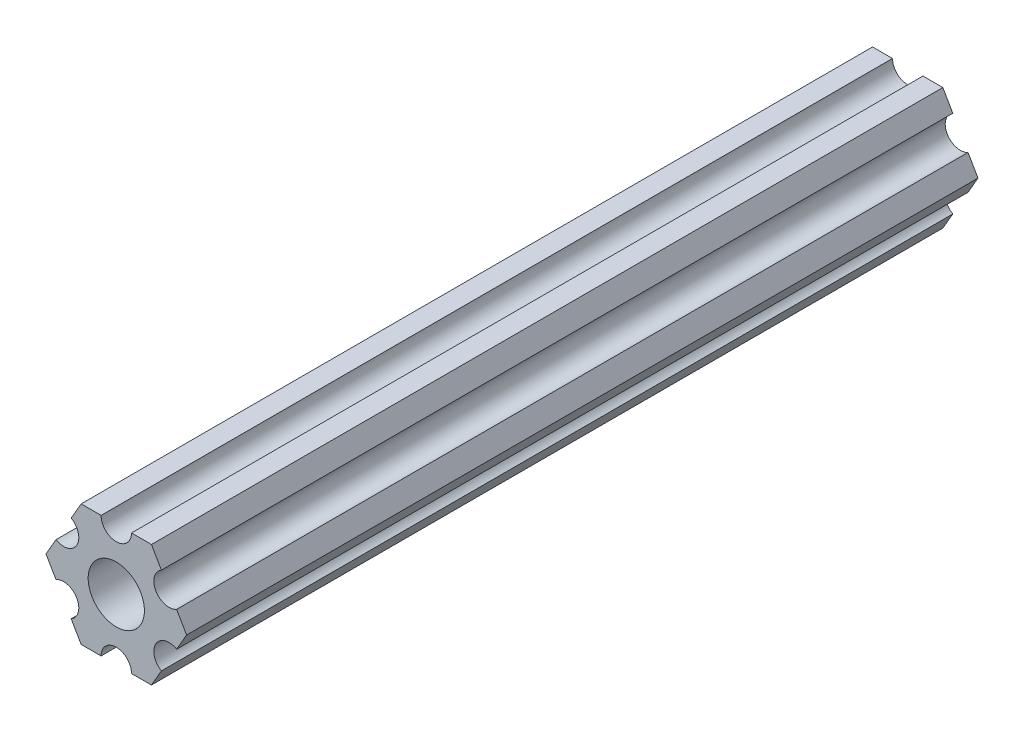
SolidWorks part; units mm, degrees
ref_plane "Front Plane" through (0, 0, 0) normal (0, 0, 1) x (1, 0, 0)
ref_plane "Top Plane" through (0, 0, 0) normal (0, 1, 0) x (1, 0, 0)
ref_plane "Right Plane" through (0, 0, 0) normal (1, 0, 0) x (0, 0, -1)
sketch "Sketch1" plane through (0, 0, 0) normal (0, 0, 1) x (1, 0, 0)
  line L0 (-4.7055, -4.5498) -> (-3.6662, -6.35)
  line L1 (7.3323, 0) -> (6.293, 1.8002)
  line L2 (3.6662, 6.35) -> (1.5875, 6.35)
  line L3 (-3.6662, 6.35) -> (-4.7055, 4.5498)
  line L4 (-7.3323, 0) -> (-6.293, -1.8002)
  line L5 (-3.6662, -6.35) -> (-1.5875, -6.35)
  line L6 (3.6662, -6.35) -> (4.7055, -4.5498)
  line L7 (-6.293, 1.8002) -> (-7.3323, 0)
  line L8 (-1.5875, 6.35) -> (-3.6662, 6.35)
  line L9 (4.7055, 4.5498) -> (3.6662, 6.35)
  line L10 (6.293, -1.8002) -> (7.3323, 0)
  line L11 (1.5875, -6.35) -> (3.6662, -6.35)
  circle A0 centre (0, 0) radius 6.35 construction
  circle A1 centre (0, 0) radius 2.9337
  arc A2 (-1.5875, 6.35) -> (1.5875, 6.35) centre (0, 6.35) ccw
  arc A3 (4.7055, 4.5498) -> (6.293, 1.8002) centre (5.4993, 3.175) ccw
  arc A4 (6.293, -1.8002) -> (4.7055, -4.5498) centre (5.4993, -3.175) ccw
  arc A5 (1.5875, -6.35) -> (-1.5875, -6.35) centre (0, -6.35) ccw
  arc A6 (-4.7055, -4.5498) -> (-6.293, -1.8002) centre (-5.4993, -3.175) ccw
  arc A7 (-6.293, 1.8002) -> (-4.7055, 4.5498) centre (-5.4993, 3.175) ccw
  point P24 (0, 0)
  dimension "D1" = 12.7
  dimension "D2" = 5.8674
  dimension "D3" = 3.175
extrude "Boss-Extrude1" add sketch "Sketch1" along normal blind 82.55
